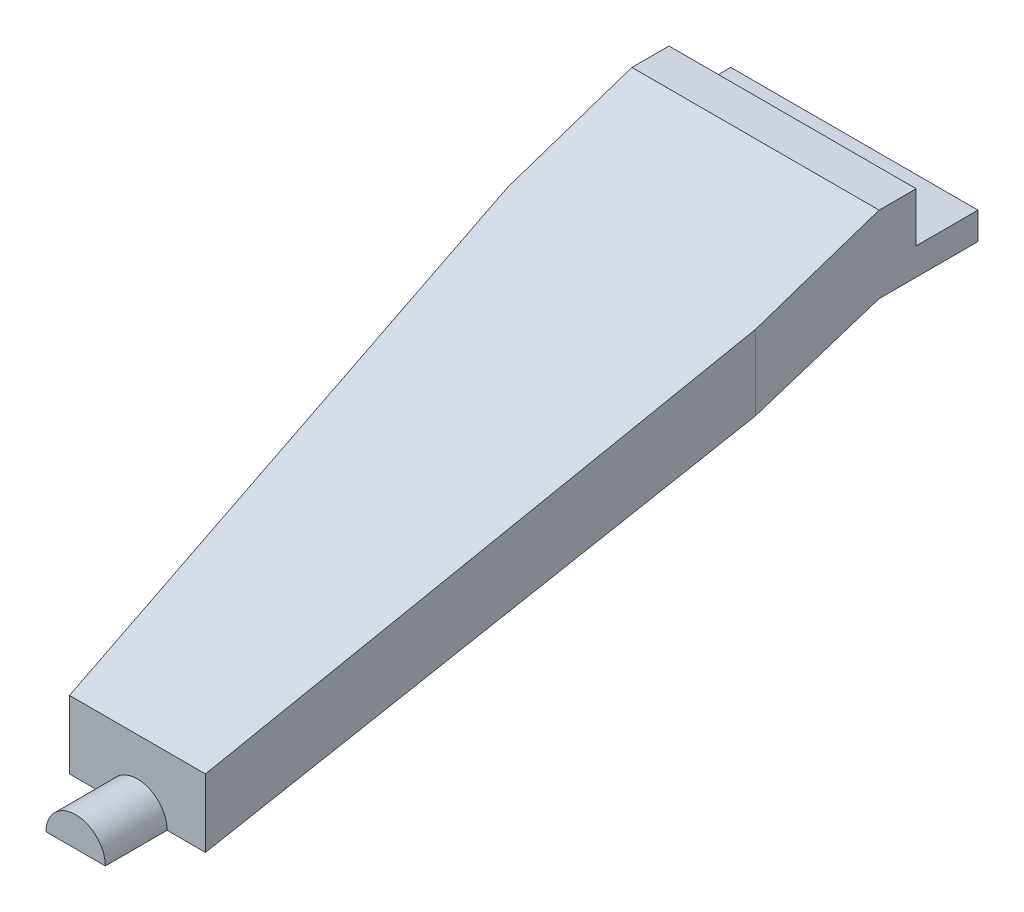
SolidWorks part; units mm, degrees
ref_plane "前视基准面" through (0, 0, 0) normal (0, 0, 1) x (1, 0, 0)
ref_plane "上视基准面" through (0, 0, 0) normal (0, 1, 0) x (1, 0, 0)
ref_plane "右视基准面" through (0, 0, 0) normal (1, 0, 0) x (0, 0, -1)
other "Configuration Table"
sketch "草图1" plane through (0, 0, 0) normal (0, 1, 0) x (1, 0, 0)
  line L1 (0, 0) -> (20, 0)
  line L2 (0, 0) -> (0, -5)
  line L3 (0, -5) -> (20, -5)
  line L4 (20, 0) -> (20, -5)
  circle A0 centre (4, -2.5) radius 0.8
  circle A1 centre (16, -2.5) radius 0.8
  point P9 (0, 0)
  dimension "D3" = 2.5
  dimension "D6" = 1.6
  dimension "D1" = 5
  dimension "D2" = 20
  dimension "D4" = 4
  dimension "D5" = 4
extrude "凸台-拉伸1" add sketch "草图1" along normal blind 2.2
sketch "草图2" plane through (0, 0, 5) normal (0, 0, 1) x (1, 0, 0)
  line L1 (0, 0) -> (20, 0)
  line L2 (0, 0) -> (0, 6.2)
  line L3 (0, 6.2) -> (20, 6.2)
  line L4 (20, 0) -> (20, 6.2)
  dimension "D1" = 6.2
  dimension "D2" = 20
extrude "凸台-拉伸2" add sketch "草图2" along normal blind 3 contours L3 L4 L1 L2
sketch "草图3" plane through (20, 0, 0) normal (1, 0, 0) x (0, 0, -1)
  line L0 (-8, 6.2) -> (-58, -10.55)
  line L1 (-58, -10.55) -> (-58, -16.05)
  line L2 (-58, -16.05) -> (-8, 0)
  line L3 (-8, 0) -> (-8, 6.2) construction
  line L5 (-58, -10.55) -> (-63, -10.55)
  line L6 (-58, -10.55) -> (-58, -16.05)
  line L7 (-58, -16.05) -> (-63, -16.05)
  line L8 (-63, -10.55) -> (-63, -16.05)
  line M7 (-8, 6.2) -> (-8, 0)
  dimension "D1" = 16.05
  dimension "D2" = 50
  dimension "D3" = 5.5
  dimension "D4" = 5
extrude "凸台-拉伸3" add sketch "草图3" against normal through all contours L1 L2 L0 M7 | L5 L8 L7 L1
sketch "草图4" plane through (0, 6.2, 0) normal (0, 1, 0) x (1, 0, 0)
  line L0 (0, -8) -> (0, -58) construction
  line L1 (20, -8) -> (0, -8)
  line L2 (20, -8) -> (20, -18)
  line L3 (20, -18) -> (0, -18)
  line L4 (0, -8) -> (0, -18)
  line L5 (0, -63) -> (20, -63) construction
  line L6 (15.5, -63) -> (4.5, -63)
  line L7 (15.5, -63) -> (15.5, -58)
  line L8 (15.5, -58) -> (4.5, -58)
  line L9 (4.5, -63) -> (4.5, -58)
  line L10 (0, -58) -> (20, -58) construction
  line L11 (15.5, -58) -> (20, -58)
  line L12 (4.5, -58) -> (0, -58)
  line L13 (0, -58) -> (0, -63) construction
  line L14 (15.5, -58) -> (20, -18)
  line L15 (4.5, -58) -> (0, -18)
  line L16 (0, -18) -> (0, -63)
  line L17 (0, -63) -> (4.5, -63)
  line L18 (15.5, -63) -> (20, -63)
  line L19 (20, -63) -> (20, -18)
  dimension "D1" = 10
  dimension "D2" = 11
extrude "切除-拉伸1" cut sketch "草图4" against normal through all contours L15 L16 L12 | L11 L19 L14 | L18 L19 L11 L7 | L16 L17 L9 L12
sketch "草图5" plane through (0, 0, 63) normal (0, 0, 1) x (1, 0, 0)
  line L0 (4.5, -16.05) -> (15.5, -16.05) construction
  line L2 (4.5, -10.55) -> (15.5, -10.55)
  line L3 (4.5, -10.55) -> (4.5, -16.05)
  line L4 (4.5, -16.05) -> (15.5, -16.05)
  line L5 (15.5, -10.55) -> (15.5, -16.05)
  circle A0 centre (10, -16.05) radius 2.4
  line M1 (4.5, -16.05) -> (15.5, -16.05)
  line M2 (15.5, -16.05) -> (15.5, -10.55)
  line M3 (15.5, -10.55) -> (4.5, -10.55)
  line M4 (4.5, -10.55) -> (4.5, -16.05)
  dimension "D1" = 4.8
extrude "切除-拉伸2" cut sketch "草图5" against normal blind 5 contours A0 M1 M2 M3 M4
